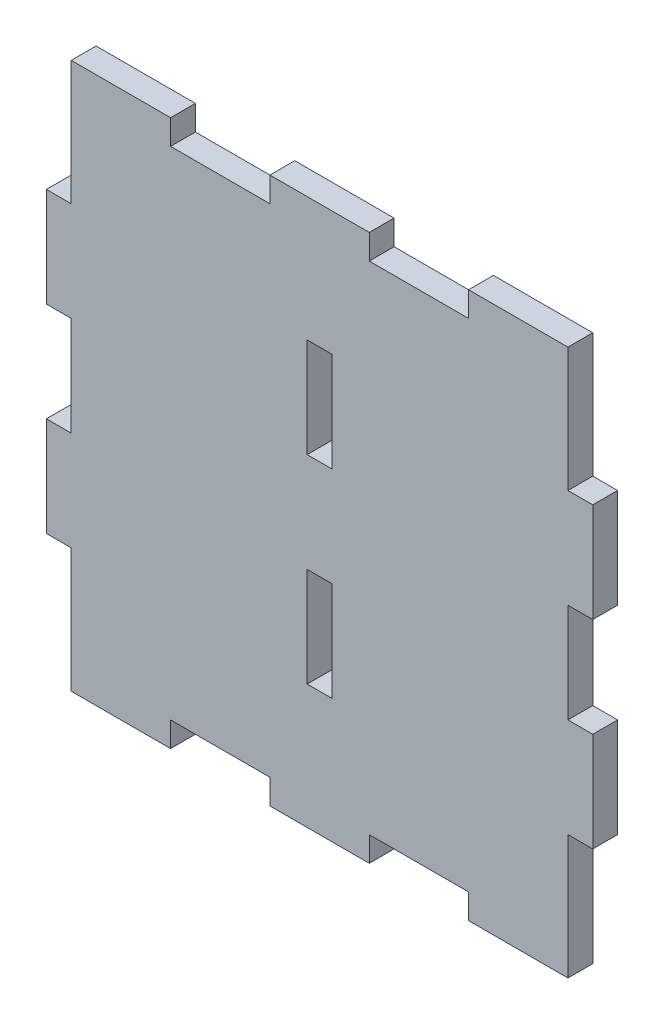
SolidWorks part; units mm, degrees
material "Pinho"
ref_plane "Plano frontal" through (0, 0, 0) normal (0, 0, 1) x (1, 0, 0)
ref_plane "Plano superior" through (0, 0, 0) normal (0, 1, 0) x (1, 0, 0)
ref_plane "Plano direito" through (0, 0, 0) normal (1, 0, 0) x (0, 0, -1)
sketch "Esboço1" plane through (0, 0, 0) normal (0, 0, 1) x (1, 0, 0)
  line L0 (-31.2169, 9.9098) -> (-31.2169, -2.0902)
  line L1 (-19.2169, 33.9098) -> (-7.2169, 33.9098)
  line L2 (-31.2169, 33.9098) -> (-31.2169, 21.9098)
  line L3 (-19.2169, -26.0902) -> (-7.2169, -26.0902)
  line L4 (28.7831, 33.9098) -> (28.7831, 21.9098)
  line L5 (-31.2169, -14.0902) -> (-31.2169, -26.0902)
  line L6 (-31.2169, 9.9098) -> (-34.2169, 9.9098)
  line L7 (4.7831, 33.9098) -> (16.7831, 33.9098)
  line L9 (-31.2169, 21.9098) -> (-34.2169, 21.9098)
  line L10 (-34.2169, 9.9098) -> (-34.2169, 21.9098)
  line L12 (-31.2169, 33.9098) -> (-31.2169, 36.9098)
  line L13 (-34.2169, -14.0902) -> (-31.2169, -14.0902)
  line L14 (-34.2169, -14.0902) -> (-34.2169, -2.0902)
  line L15 (-34.2169, -2.0902) -> (-31.2169, -2.0902)
  line L17 (-31.2169, 36.9098) -> (-19.2169, 36.9098)
  line L18 (-19.2169, 33.9098) -> (-19.2169, 36.9098)
  line L20 (28.7831, 33.9098) -> (28.7831, 36.9098)
  line L21 (28.7831, 36.9098) -> (16.7831, 36.9098)
  line L22 (16.7831, 33.9098) -> (16.7831, 36.9098)
  line L24 (-7.2169, 33.9098) -> (-7.2169, 36.9098)
  line L25 (-7.2169, 36.9098) -> (4.7831, 36.9098)
  line L26 (4.7831, 33.9098) -> (4.7831, 36.9098)
  line L27 (28.7831, -14.0902) -> (28.7831, -26.0902)
  line L28 (28.7831, 9.9098) -> (31.7831, 9.9098)
  line L30 (28.7831, 21.9098) -> (31.7831, 21.9098)
  line L31 (31.7831, 9.9098) -> (31.7831, 21.9098)
  line L32 (4.7831, -26.0902) -> (16.7831, -26.0902)
  line L34 (28.7831, -14.0902) -> (31.7831, -14.0902)
  line L36 (28.7831, -2.0902) -> (31.7831, -2.0902)
  line L37 (31.7831, -14.0902) -> (31.7831, -2.0902)
  line L38 (28.7831, 9.9098) -> (28.7831, -2.0902)
  line L39 (-31.2169, -26.0902) -> (-31.2169, -29.0902)
  line L40 (-31.2169, -29.0902) -> (-19.2169, -29.0902)
  line L41 (-19.2169, -26.0902) -> (-19.2169, -29.0902)
  line L43 (28.7831, -26.0902) -> (28.7831, -29.0902)
  line L44 (28.7831, -29.0902) -> (16.7831, -29.0902)
  line L45 (16.7831, -26.0902) -> (16.7831, -29.0902)
  line L47 (-7.2169, -26.0902) -> (-7.2169, -29.0902)
  line L48 (-7.2169, -29.0902) -> (4.7831, -29.0902)
  line L49 (4.7831, -26.0902) -> (4.7831, -29.0902)
  line L50 (-1.2169, -29.0902) -> (-1.2169, 36.9098) construction
  line L52 (-2.7169, -2.0902) -> (0.2831, -2.0902)
  line L53 (-2.7169, -2.0902) -> (-2.7169, -14.0902)
  line L54 (-2.7169, -14.0902) -> (0.2831, -14.0902)
  line L55 (0.2831, -2.0902) -> (0.2831, -14.0902)
  line L56 (-2.7169, -2.0902) -> (0.2831, -14.0902) construction
  line L57 (-2.7169, -14.0902) -> (0.2831, -2.0902) construction
  line L58 (-2.7169, 21.9098) -> (0.2831, 21.9098)
  line L59 (-2.7169, 21.9098) -> (-2.7169, 9.9098)
  line L60 (-2.7169, 9.9098) -> (0.2831, 9.9098)
  line L61 (0.2831, 21.9098) -> (0.2831, 9.9098)
  line L62 (-2.7169, 21.9098) -> (0.2831, 9.9098) construction
  line L63 (-2.7169, 9.9098) -> (0.2831, 21.9098) construction
  point P0 (0, 0)
  point P22 (-1.2169, -8.0902)
  point P49 (-1.2169, 15.9098)
  dimension "D1" = 60
  dimension "D2" = 60
  dimension "D3" = 12
  dimension "D4" = 12
  dimension "D5" = 12
  dimension "D6" = 12
  dimension "D7" = 12
  dimension "D8" = 12
  dimension "D9" = 12
  dimension "D10" = 12
  dimension "D11" = 12
  dimension "D12" = 12
  dimension "D13" = 12
  dimension "D14" = 12
  dimension "D15" = 12
  dimension "D16" = 12
  dimension "D17" = 3
  dimension "D18" = 3
  dimension "D19" = 3
  dimension "D20" = 3
  dimension "D21" = 3
  dimension "D22" = 3
  dimension "D23" = 3
  dimension "D24" = 3
  dimension "D25" = 3
  dimension "D26" = 3
  dimension "D27" = 3
  dimension "D28" = 3
  dimension "D29" = 3
  dimension "D30" = 12
  dimension "D31" = 3
  dimension "D32" = 12
  dimension "D33" = 12
  dimension "D34" = 12
  dimension "D35" = 12
  dimension "D36" = 3
  dimension "D37" = 3
extrude "Ressalto-extrusão1" add sketch "Esboço1" along normal blind 3
